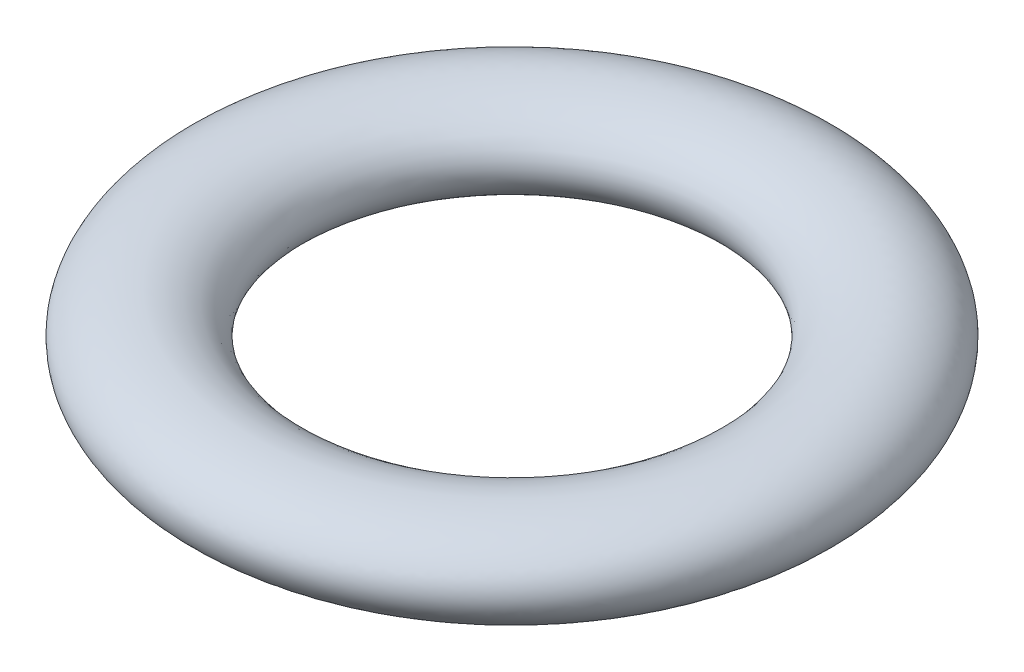
SolidWorks part; units mm, degrees
ref_plane "Front Plane" through (0, 0, 0) normal (0, 0, 1) x (1, 0, 0)
ref_plane "Top Plane" through (0, 0, 0) normal (0, 1, 0) x (1, 0, 0)
ref_plane "Right Plane" through (0, 0, 0) normal (1, 0, 0) x (0, 0, -1)
sketch "Reconstructed nominal axial profile" plane through (0, 0, 0) normal (0, 0, 1) x (1, 0, 0)
  line L0 (0, -500) -> (0, 50) construction
  ellipse E0 centre (12, 0) end of major axis (14.9948, 0) minor radius 2
revolve "Native revolved geometry" add sketch "Reconstructed nominal axial profile" angle 360 about L0
